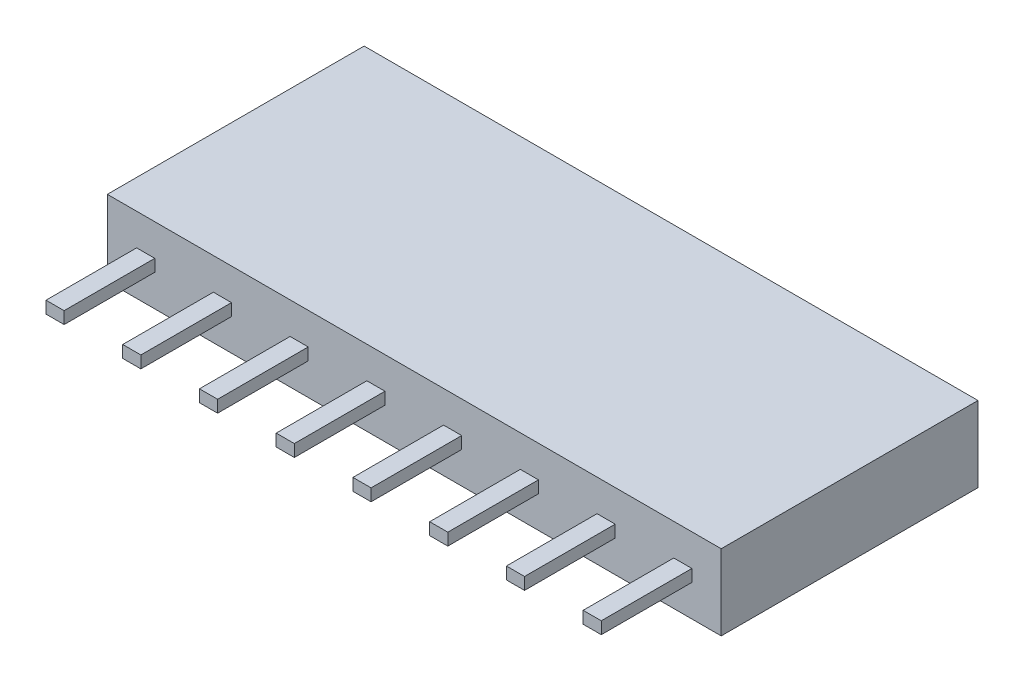
SolidWorks part; units mm, degrees
ref_plane "Front" through (0, 0, 0) normal (0, 0, 1) x (1, 0, 0)
ref_plane "Top" through (0, 0, 0) normal (0, 1, 0) x (1, 0, 0)
ref_plane "Right" through (0, 0, 0) normal (1, 0, 0) x (0, 0, -1)
sketch "Эскиз1" plane through (0, 0, 0) normal (0, 1, 0) x (1, 0, 0)
  line L1 (-10.16, 4.25) -> (10.16, 4.25)
  line L2 (-10.16, 4.25) -> (-10.16, -4.25)
  line L3 (-10.16, -4.25) -> (10.16, -4.25)
  line L4 (10.16, 4.25) -> (10.16, -4.25)
  line L5 (-10.16, 4.25) -> (10.16, -4.25) construction
  line L6 (-10.16, -4.25) -> (10.16, 4.25) construction
  point P0 (0, 0)
extrude "Бобышка-Вытянуть1" add sketch "Эскиз1" along normal blind 2.5
sketch "Эскиз2" plane through (0, 0, 4.25) normal (0, 0, 1) x (1, 0, 0)
  line L0 (-10.16, 1.25) -> (10.16, 1.25) construction
  line L1 (-10.16, 2.5) -> (-10.16, 0) construction
  line L2 (10.16, 2.5) -> (10.16, 0) construction
  line L3 (-6.65, 1.05) -> (-6.05, 1.05)
  line L4 (-9.19, 1.05) -> (-8.59, 1.05)
  line L5 (-9.19, 1.05) -> (-9.19, 1.45)
  line L6 (-9.19, 1.45) -> (-8.59, 1.45)
  line L7 (-8.59, 1.05) -> (-8.59, 1.45)
  line L8 (-9.19, 1.05) -> (-8.59, 1.45) construction
  line L9 (-9.19, 1.45) -> (-8.59, 1.05) construction
  line L10 (-6.65, 1.05) -> (-6.05, 1.45) construction
  line L11 (-6.65, 1.05) -> (-6.65, 1.45)
  line L12 (-6.65, 1.45) -> (-6.05, 1.45)
  line L13 (-6.65, 1.45) -> (-6.05, 1.05) construction
  line L14 (-6.05, 1.05) -> (-6.05, 1.45)
  line L15 (-4.11, 1.05) -> (-3.51, 1.05)
  line L16 (-4.11, 1.05) -> (-3.51, 1.45) construction
  line L17 (-4.11, 1.05) -> (-4.11, 1.45)
  line L18 (-4.11, 1.45) -> (-3.51, 1.45)
  line L19 (-4.11, 1.45) -> (-3.51, 1.05) construction
  line L20 (-3.51, 1.05) -> (-3.51, 1.45)
  line L21 (-1.57, 1.05) -> (-0.97, 1.05)
  line L22 (-1.57, 1.05) -> (-0.97, 1.45) construction
  line L23 (-1.57, 1.05) -> (-1.57, 1.45)
  line L24 (-1.57, 1.45) -> (-0.97, 1.45)
  line L25 (-1.57, 1.45) -> (-0.97, 1.05) construction
  line L26 (-0.97, 1.05) -> (-0.97, 1.45)
  line L27 (0.97, 1.05) -> (1.57, 1.05)
  line L28 (0.97, 1.05) -> (1.57, 1.45) construction
  line L29 (0.97, 1.05) -> (0.97, 1.45)
  line L30 (0.97, 1.45) -> (1.57, 1.45)
  line L31 (0.97, 1.45) -> (1.57, 1.05) construction
  line L32 (1.57, 1.05) -> (1.57, 1.45)
  line L33 (3.51, 1.05) -> (4.11, 1.05)
  line L34 (3.51, 1.05) -> (4.11, 1.45) construction
  line L35 (3.51, 1.05) -> (3.51, 1.45)
  line L36 (3.51, 1.45) -> (4.11, 1.45)
  line L37 (3.51, 1.45) -> (4.11, 1.05) construction
  line L38 (4.11, 1.05) -> (4.11, 1.45)
  line L39 (6.05, 1.05) -> (6.65, 1.05)
  line L40 (6.05, 1.05) -> (6.65, 1.45) construction
  line L41 (6.05, 1.05) -> (6.05, 1.45)
  line L42 (6.05, 1.45) -> (6.65, 1.45)
  line L43 (6.05, 1.45) -> (6.65, 1.05) construction
  line L44 (6.65, 1.05) -> (6.65, 1.45)
  line L45 (8.59, 1.05) -> (9.19, 1.05)
  line L46 (8.59, 1.05) -> (9.19, 1.45) construction
  line L47 (8.59, 1.05) -> (8.59, 1.45)
  line L48 (8.59, 1.45) -> (9.19, 1.45)
  line L49 (8.59, 1.45) -> (9.19, 1.05) construction
  line L50 (9.19, 1.05) -> (9.19, 1.45)
  dimension "D1" = 8
extrude "Бобышка-Вытянуть2" add sketch "Эскиз2" along normal blind 3
sketch "Эскиз3" plane through (0, 1.05, 0) normal (0, -1, 0) x (1, 0, 0)
  line L0 (-8.59, 7.25) -> (-8.59, 4.25) construction
  line L1 (-9.19, 7.25) -> (-8.59, 7.25)
  line L2 (-9.19, 7.25) -> (-9.19, 5.55)
  line L3 (-9.19, 5.55) -> (-8.59, 5.55)
  line L4 (-8.59, 7.25) -> (-8.59, 5.55)
  line L5 (-6.65, 7.25) -> (-6.05, 7.25)
  line L6 (-6.65, 7.25) -> (-6.65, 5.55)
  line L7 (-6.65, 5.55) -> (-6.05, 5.55)
  line L8 (-6.05, 7.25) -> (-6.05, 5.55)
  line L9 (-4.11, 7.25) -> (-3.51, 7.25)
  line L10 (-4.11, 7.25) -> (-4.11, 5.55)
  line L11 (-4.11, 5.55) -> (-3.51, 5.55)
  line L12 (-3.51, 7.25) -> (-3.51, 5.55)
  line L13 (-1.57, 7.25) -> (-0.97, 7.25)
  line L14 (-1.57, 7.25) -> (-1.57, 5.55)
  line L15 (-1.57, 5.55) -> (-0.97, 5.55)
  line L16 (-0.97, 7.25) -> (-0.97, 5.55)
  line L17 (0.97, 7.25) -> (1.57, 7.25)
  line L18 (0.97, 7.25) -> (0.97, 5.55)
  line L19 (0.97, 5.55) -> (1.57, 5.55)
  line L20 (1.57, 7.25) -> (1.57, 5.55)
  line L21 (3.51, 7.25) -> (4.11, 7.25)
  line L22 (3.51, 7.25) -> (3.51, 5.55)
  line L23 (3.51, 5.55) -> (4.11, 5.55)
  line L24 (4.11, 7.25) -> (4.11, 5.55)
  line L25 (6.05, 7.25) -> (6.65, 7.25)
  line L26 (6.05, 7.25) -> (6.05, 5.55)
  line L27 (6.05, 5.55) -> (6.65, 5.55)
  line L28 (6.65, 7.25) -> (6.65, 5.55)
  line L29 (8.59, 7.25) -> (9.19, 7.25)
  line L30 (8.59, 7.25) -> (8.59, 5.55)
  line L31 (8.59, 5.55) -> (9.19, 5.55)
  line L32 (9.19, 7.25) -> (9.19, 5.55)
  dimension "D1" = 8
